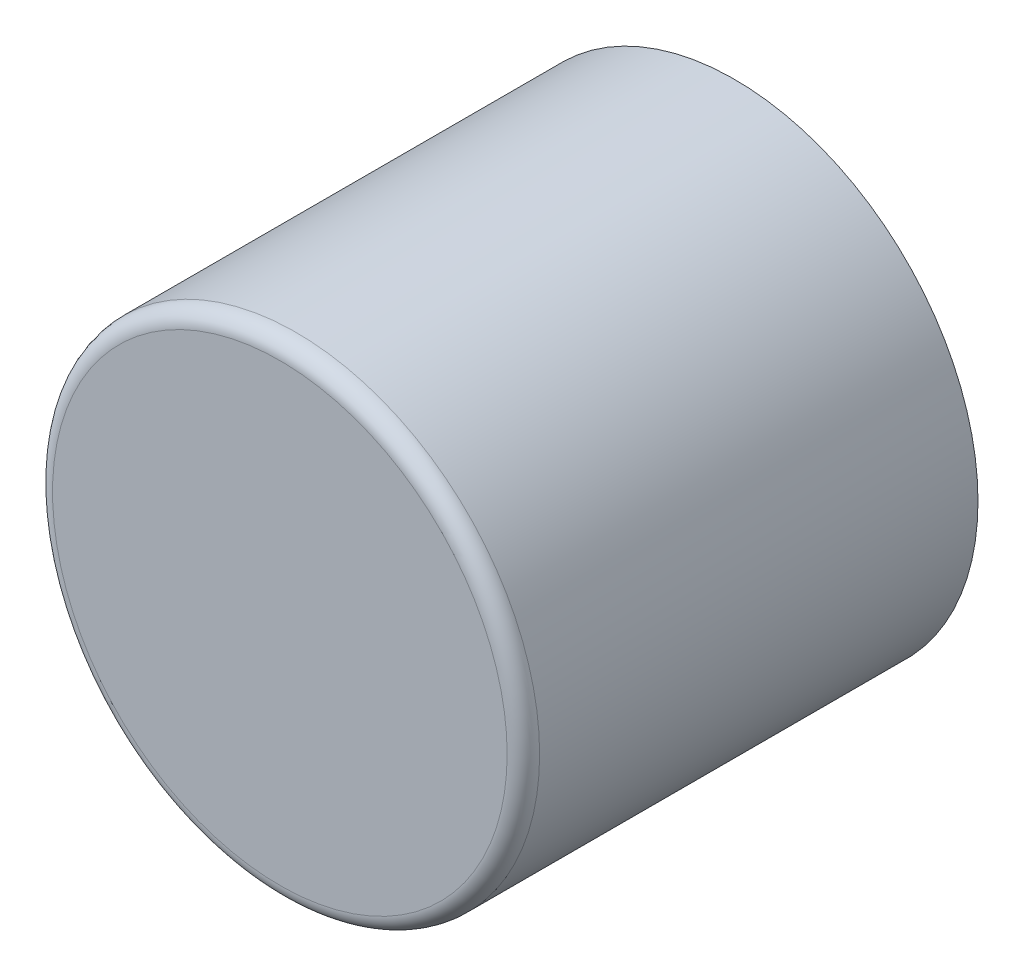
SolidWorks part; units mm, degrees
material "Brass"
ref_plane "Front Plane" through (0, 0, 0) normal (0, 0, 1) x (1, 0, 0)
ref_plane "Top Plane" through (0, 0, 0) normal (0, 1, 0) x (1, 0, 0)
ref_plane "Right Plane" through (0, 0, 0) normal (1, 0, 0) x (0, 0, -1)
sketch "Sketch1" plane through (0, 0, 0) normal (0, 0, 1) x (1, 0, 0)
  circle A0 centre (0, 0) radius 7.5
  dimension "D1" = 15
extrude "Boss-Extrude1" add sketch "Sketch1" along normal blind 14
hole_wizard "M8x1.0 Tapped Hole1" positions "Sketch2" profile "Sketch3" tap size "M8x1.0" standard "ANSI Metric"
sketch "Sketch2" plane through (0, 0, 0) normal (0, 0, -1) x (-1, 0, 0)
  point P0 (0, 0)
sketch "Sketch3" plane through (0, 0, 0) normal (1, 0, 0) x (0, 1, 0)
  line L0 (0, 0) -> (0, 12.0207)
  line L1 (0, 12.0207) -> (3.5, 10)
  line L2 (3.5, 10) -> (3.5, 0)
  line L5 (3.5, 0) -> (0, 0)
  line L10 (0, 12.0207) -> (-3.5, 10) construction
  line L11 (0, -6.35) -> (0, 107.95) construction
  dimension "Tap Drill Dia." = 7
  dimension "Tap Drill Depth" = 10
  dimension "Drill Angle" = 120
cosmetic thread "Hole Thread1" parameters "D1"=8, "D2"=8
fillet "Fillet1" radius 0.5 1 edges at (7.5, 0, 14)
